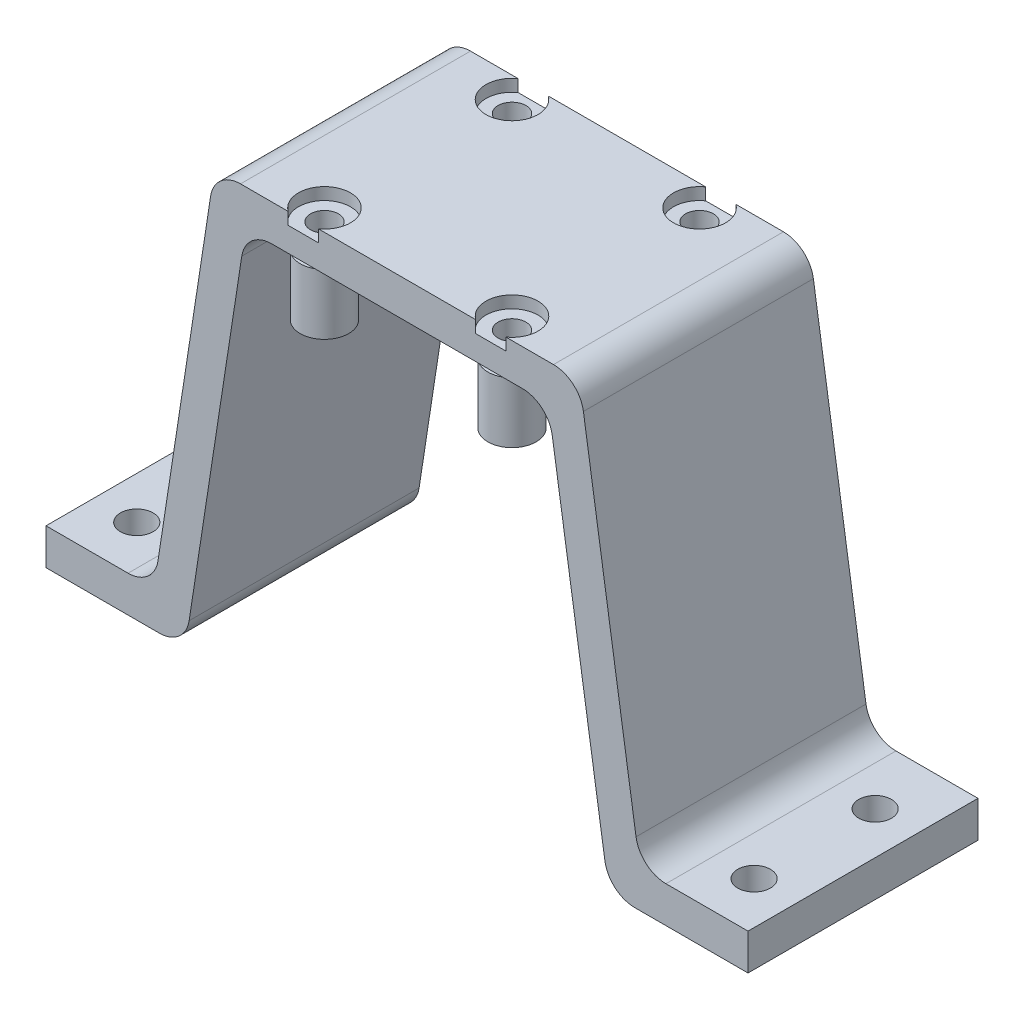
SolidWorks part; units mm, degrees
material "ABS"
ref_plane "前视基准面" through (0, 0, 0) normal (0, 0, 1) x (1, 0, 0)
ref_plane "上视基准面" through (0, 0, 0) normal (0, 1, 0) x (1, 0, 0)
ref_plane "右视基准面" through (0, 0, 0) normal (1, 0, 0) x (0, 0, -1)
sketch "草图1" plane through (0, 0, 0) normal (0, 0, 1) x (1, 0, 0)
  line L0 (-20.0738, 0) -> (-15.0738, 32.5)
  line L1 (-15.0738, 32.5) -> (15.0738, 32.5)
  line L2 (15.0738, 32.5) -> (20.0738, 0)
  line L4 (17.5, -3) -> (12.5, 29.5)
  line L5 (12.5, 29.5) -> (-12.5, 29.5)
  line L6 (-12.5, 29.5) -> (-17.5, -3)
  line L8 (-20.0738, 0) -> (-29, 0)
  line L9 (-29, 0) -> (-29, -3)
  line L10 (-29, -3) -> (-17.5, -3)
  line L12 (20.0738, 0) -> (29, 0)
  line L13 (29, 0) -> (29, -3)
  line L14 (29, -3) -> (17.5, -3)
  point P10 (0, 32.5)
  point P11 (0, 29.5)
  dimension "D1" = 25
  dimension "D2" = 3
  dimension "D3" = 3
  dimension "D4" = 29.5
  dimension "D5" = 35
  dimension "D6" = 58
  dimension "D7" = 3
extrude "凸台-拉伸1" add sketch "草图1" along normal mid plane 19
sketch "草图2" plane through (0, 29.5, 0) normal (0, -1, 0) x (1, 0, 0)
  line L1 (-7.747, 7.747) -> (7.747, 7.747) construction
  line L2 (-7.747, 7.747) -> (-7.747, -7.747) construction
  line L3 (-7.747, -7.747) -> (7.747, -7.747) construction
  line L4 (7.747, 7.747) -> (7.747, -7.747) construction
  line L5 (-10.033, 10.033) -> (10.033, 10.033) construction
  line L6 (-10.033, 10.033) -> (-10.033, -10.033) construction
  line L7 (-10.033, -10.033) -> (10.033, -10.033) construction
  line L8 (10.033, 10.033) -> (10.033, -10.033) construction
  circle A0 centre (-7.747, 7.747) radius 1.15
  circle A1 centre (7.747, 7.747) radius 1.15
  circle A2 centre (7.747, -7.747) radius 1.15
  circle A3 centre (-7.747, -7.747) radius 1.15
  point P4 (0, 7.747)
  point P6 (-7.747, 0)
  point P15 (0, 10.033)
  point P16 (-10.033, 0)
  dimension "D1" = 2.3
  dimension "D2" = 20.066
  dimension "D3" = 2.286
extrude "切除-拉伸1" cut sketch "草图2" against normal through all
sketch "草图3" plane through (0, 29.5, 0) normal (0, -1, 0) x (1, 0, 0)
  circle A0 centre (-7.747, 7.747) radius 2
  circle A1 centre (7.747, 7.747) radius 2
  circle A2 centre (7.747, -7.747) radius 2
  circle A3 centre (-7.747, -7.747) radius 2
  circle A4 centre (-7.747, 7.747) radius 1.15 construction
  circle A5 centre (-7.747, 7.747) radius 1.15
  circle A6 centre (-7.747, -7.747) radius 1.15 construction
  circle A7 centre (7.747, -7.747) radius 1.15 construction
  circle A8 centre (7.747, 7.747) radius 1.15 construction
  circle A9 centre (-7.747, -7.747) radius 1.15
  circle A10 centre (7.747, -7.747) radius 1.15
  circle A11 centre (7.747, 7.747) radius 1.15
  dimension "D1" = 4
extrude "凸台-拉伸2" add sketch "草图3" along normal blind 5
sketch "草图4" plane through (0, 0, 0) normal (0, 1, 0) x (1, 0, 0)
  line L0 (-20.0738, 9.5) -> (-29, 9.5) construction
  line L2 (-25.5, 4.5) -> (0, 4.5) construction
  line L3 (0, 4.5) -> (25.5, 4.5) construction
  circle A0 centre (-25.5, 4.5) radius 1.35
  circle A1 centre (-25.5, -5.5) radius 1.35
  circle A2 centre (25.5, 4.5) radius 1.35
  circle A3 centre (25.5, -5.5) radius 1.35
  dimension "D1" = 2.7
  dimension "D2" = 25.5
  dimension "D4" = 5
  dimension "D5" = 10
extrude "切除-拉伸2" cut sketch "草图4" against normal through all
fillet "圆角1" radius 2.5 8 edges at (17.5, -3, 0) (-17.5, -3, 0) (-20.0738, 0, 0) (20.0738, 0, 0) (-12.5, 29.5, 0) (12.5, 29.5, 0) (15.0738, 32.5, 0) (-15.0738, 32.5, 0)
sketch "草图5" plane through (0, 32.5, 0) normal (0, 1, 0) x (1, 0, 0)
  circle A0 centre (-7.747, -7.747) radius 2.15
  circle A1 centre (7.747, -7.747) radius 2.15
  circle A2 centre (7.747, 7.747) radius 2.15
  circle A3 centre (-7.747, 7.747) radius 2.15
  dimension "D1" = 4.3
extrude "切除-拉伸3" cut sketch "草图5" against normal blind 1
